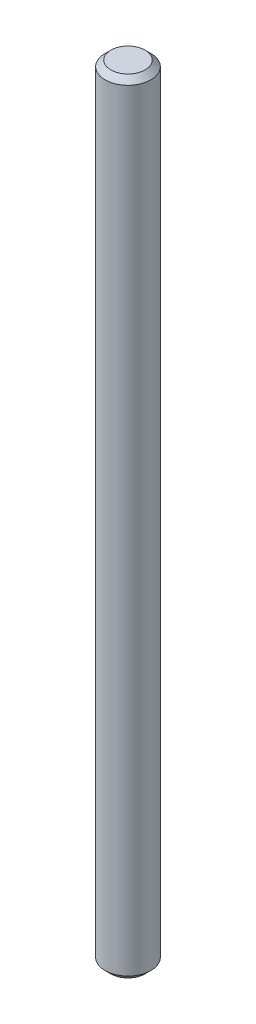
SolidWorks part; units mm, degrees
ref_plane "Front Plane" through (0, 0, 0) normal (0, 0, 1) x (1, 0, 0)
ref_plane "Top Plane" through (0, 0, 0) normal (0, 1, 0) x (1, 0, 0)
ref_plane "Right Plane" through (0, 0, 0) normal (1, 0, 0) x (0, 0, -1)
sketch "Sketch1" plane through (0, 0, 0) normal (0, 1, 0) x (1, 0, 0)
  circle A0 centre (0, 0) radius 3.175
  dimension "D1" = 6.35
extrude "Boss-Extrude1" add sketch "Sketch1" along normal blind 108.585
chamfer "Chamfer1" distance 0.7937 angle 45 2 edges at (0, 0, 3.175) (0, 108.585, 3.175)
